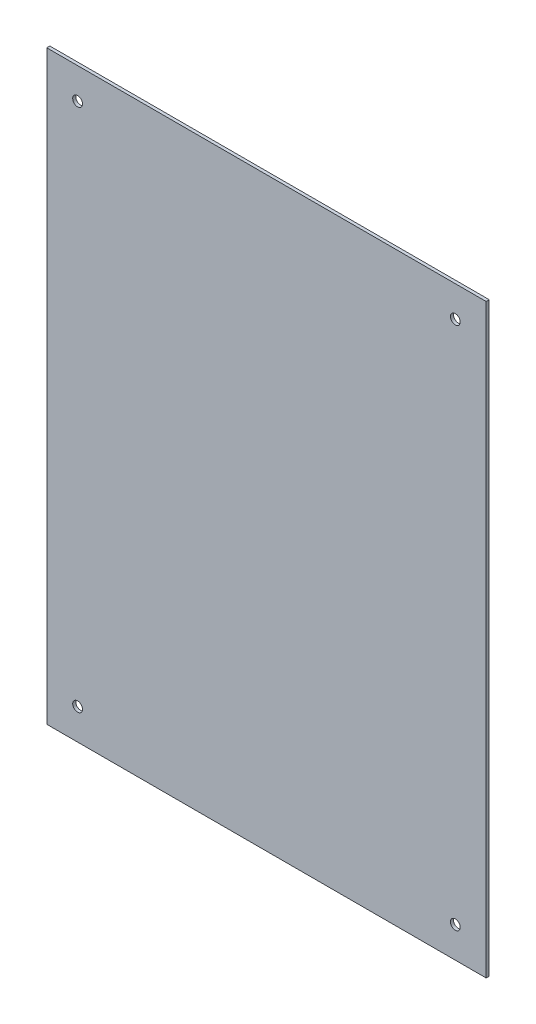
SolidWorks part; units mm, degrees
ref_plane "Alzado" through (0, 0, 0) normal (0, 0, 1) x (1, 0, 0)
ref_plane "Planta" through (0, 0, 0) normal (0, 1, 0) x (1, 0, 0)
ref_plane "Vista lateral" through (0, 0, 0) normal (1, 0, 0) x (0, 0, -1)
sketch "Croquis1" plane through (0, 0, 0) normal (0, 0, 1) x (1, 0, 0)
  line L0 (62.5, 5) -> (62.5, 431) construction
  line L3 (62.5, 431) -> (62.5, 218) construction
  line L4 (62.5, 218) -> (106.7661, 218) construction
  line L6 (-80, 408) -> (205, 408)
  line L7 (-80, 408) -> (-80, 28)
  line L8 (-80, 28) -> (205, 28)
  line L9 (205, 408) -> (205, 28)
  line L10 (-80, 408) -> (205, 28) construction
  line L11 (-80, 28) -> (205, 408) construction
  dimension "D1" = 285
  dimension "D2" = 380
extrude "Saliente-Extruir1" add sketch "Croquis1" along normal blind 2
sketch "Croquis2" plane through (0, 0, 2) normal (0, 0, 1) x (1, 0, 0)
  line L0 (-80, 218) -> (205, 218) construction
  line L1 (-80, 408) -> (-80, 28) construction
  line L2 (205, 28) -> (205, 408) construction
  line L3 (205, 218) -> (62.5, 218) construction
  line L4 (62.5, 218) -> (62.5, 408) construction
  line L5 (205, 408) -> (-80, 408) construction
  line L7 (-60, 388) -> (185, 388) construction
  line L8 (-60, 388) -> (-60, 48) construction
  line L9 (-60, 48) -> (185, 48) construction
  line L10 (185, 388) -> (185, 48) construction
  line L11 (-60, 388) -> (185, 48) construction
  line L12 (-60, 48) -> (185, 388) construction
  circle A0 centre (-60, 388) radius 3.175
  circle A1 centre (185, 388) radius 3.175
  circle A2 centre (185, 48) radius 3.175
  circle A3 centre (-60, 48) radius 3.175
  dimension "D3" = 6.35
  dimension "D1" = 20
  dimension "D2" = 20
extrude "Cortar-Extruir1" cut sketch "Croquis2" against normal blind 10
